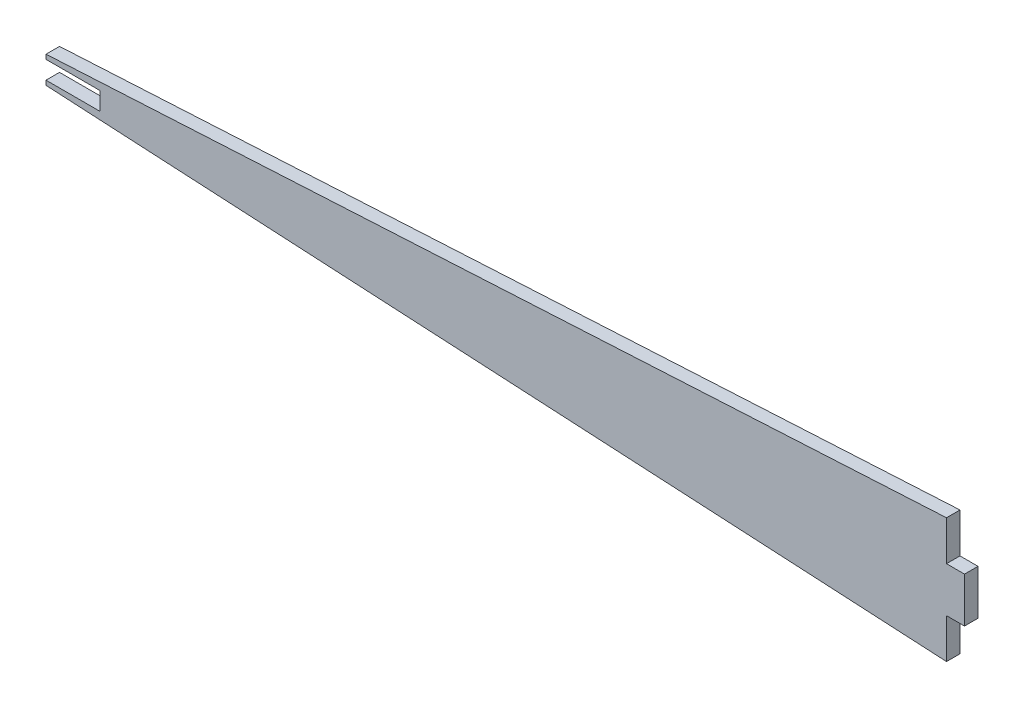
SolidWorks part; units mm, degrees
ref_plane "前视基准面" through (0, 0, 0) normal (0, 0, 1) x (1, 0, 0)
ref_plane "上视基准面" through (0, 0, 0) normal (0, 1, 0) x (1, 0, 0)
ref_plane "右视基准面" through (0, 0, 0) normal (1, 0, 0) x (0, 0, -1)
sketch "Model" plane through (0, 0, 0) normal (0, 0, 1) x (1, 0, 0)
  line L0 (100.8186, 0.5888) -> (100.8186, 5.0104)
  line L1 (100.8186, 10.0104) -> (102.8186, 10.0104)
  line L2 (102.8186, 10.0104) -> (102.8186, 5.0104)
  line L3 (102.8186, 5.0104) -> (100.8186, 5.0104)
  line L4 (100.8186, 10.0104) -> (100.8186, 14.432)
  line L5 (100.8186, 0.5888) -> (0.7594, 6.0104)
  line L6 (0.7594, 9.0104) -> (100.8186, 14.432)
  line L7 (6.7594, 7.5104) -> (6.7594, 6.5104)
  line L8 (6.7594, 7.5104) -> (6.7594, 8.5104)
  line L9 (0.7594, 8.5104) -> (6.7594, 8.5104)
  line L10 (0.7594, 6.5104) -> (6.7594, 6.5104)
  line L11 (0.7594, 9.0104) -> (0.7594, 8.5104)
  line L12 (0.7594, 6.5104) -> (0.7594, 6.0104)
extrude "凸台-拉伸1" add sketch "Model" along normal blind 1.5
